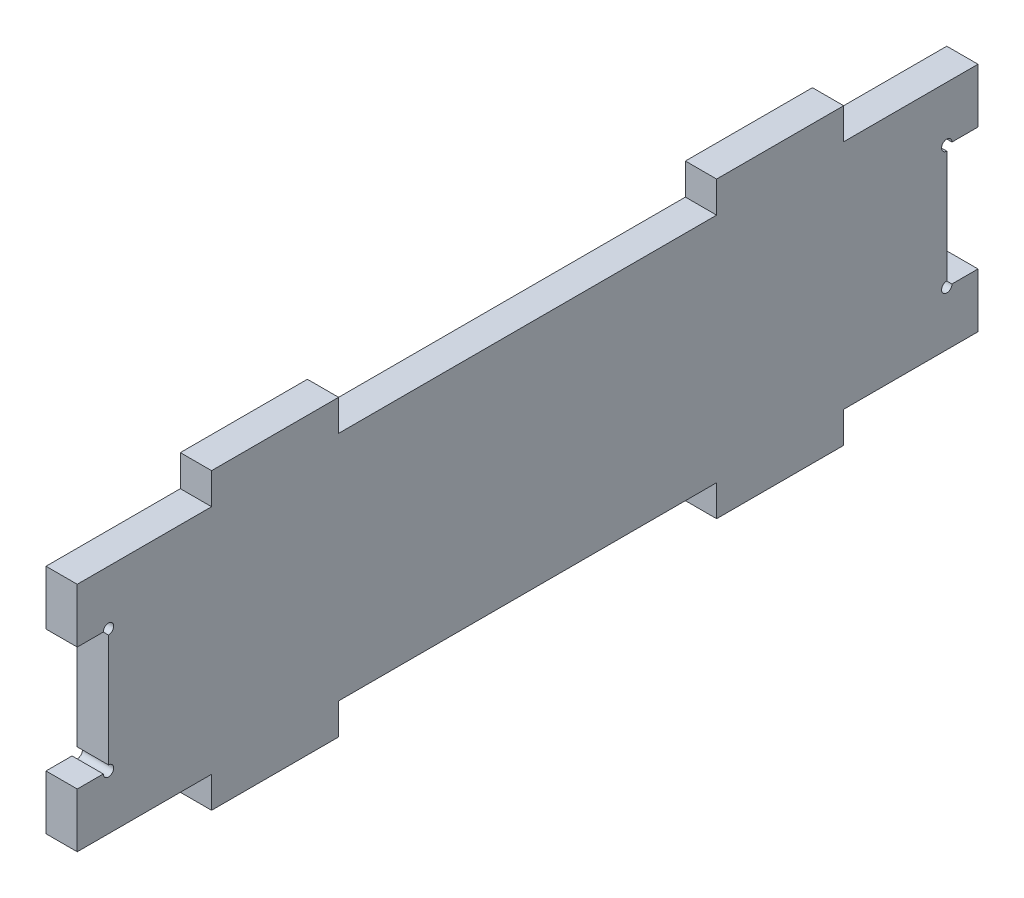
SolidWorks part; units mm, degrees
material "Acrylic (Medium-high impact)"
ref_plane "Front Plane" through (0, 0, 0) normal (0, 0, 1) x (1, 0, 0)
ref_plane "Top Plane" through (0, 0, 0) normal (0, 1, 0) x (1, 0, 0)
ref_plane "Right Plane" through (0, 0, 0) normal (1, 0, 0) x (0, 0, -1)
sketch "Sketch3" plane through (0, 0, 0) normal (1, 0, 0) x (0, 0, -1)
  line L0 (61.543, 28.3197) -> (73.743, 28.3197)
  line L1 (13.043, 0.0697) -> (25.243, 0.0697)
  line L2 (0.143, 3.0697) -> (0.143, 8.2947)
  line L3 (13.043, 28.3197) -> (25.243, 28.3197)
  line L4 (86.643, 3.0697) -> (86.643, 8.2947)
  line L5 (0.143, 20.0947) -> (0.143, 25.3197)
  line L6 (13.043, 28.3197) -> (13.043, 25.3197)
  line L7 (25.243, 25.3197) -> (61.543, 25.3197)
  line L8 (25.243, 28.3197) -> (25.243, 25.3197)
  line L9 (0.143, 20.0947) -> (2.643, 20.0947)
  line L10 (61.543, 28.3197) -> (61.543, 25.3197)
  line L11 (73.743, 25.3197) -> (86.643, 25.3197)
  line L12 (73.743, 28.3197) -> (73.743, 25.3197)
  line L13 (0.143, 25.3197) -> (13.043, 25.3197)
  line L14 (86.643, 20.0947) -> (86.643, 25.3197)
  line L15 (0.143, 3.0697) -> (13.043, 3.0697)
  line L16 (0.143, 8.2947) -> (2.643, 8.2947)
  line L17 (61.543, 0.0697) -> (73.743, 0.0697)
  line L18 (3.143, 19.5947) -> (3.143, 8.7947)
  line L19 (13.043, 3.0697) -> (13.043, 0.0697)
  line L20 (86.643, 20.0947) -> (84.143, 20.0947)
  line L21 (25.243, 3.0697) -> (25.243, 0.0697)
  line L22 (73.743, 3.0697) -> (86.643, 3.0697)
  line L23 (61.543, 3.0697) -> (61.543, 0.0697)
  line L25 (73.743, 3.0697) -> (73.743, 0.0697)
  line L26 (25.243, 3.0697) -> (61.543, 3.0697)
  line L27 (86.643, 8.2947) -> (84.143, 8.2947)
  line L28 (83.643, 19.5947) -> (83.643, 8.7947)
  arc A0 (3.143, 19.5947) -> (2.643, 20.0947) centre (3.143, 20.0947) ccw
  arc A1 (2.643, 8.2947) -> (3.143, 8.7947) centre (3.143, 8.2947) ccw
  arc A2 (83.643, 8.7947) -> (84.143, 8.2947) centre (83.643, 8.2947) ccw
  arc A3 (84.143, 20.0947) -> (83.643, 19.5947) centre (83.643, 20.0947) ccw
  dimension "D19" = 1
  dimension "D1" = 22.25
  dimension "D2" = 12.9
  dimension "D3" = 12.9
  dimension "D4" = 86.5
  dimension "D5" = 12.2
  dimension "D6" = 12.2
  dimension "D7" = 12.9
  dimension "D8" = 12.2
  dimension "D9" = 12.9
  dimension "D10" = 12.2
  dimension "D11" = 28.25
  dimension "D12" = 11.8
  dimension "D13" = 5.225
  dimension "D14" = 3
  dimension "D15" = 3
  dimension "D16" = 3
  dimension "D17" = 5.225
  dimension "D18" = 11.8
extrude "Boss-Extrude1" add sketch "Sketch3" along normal blind 3
